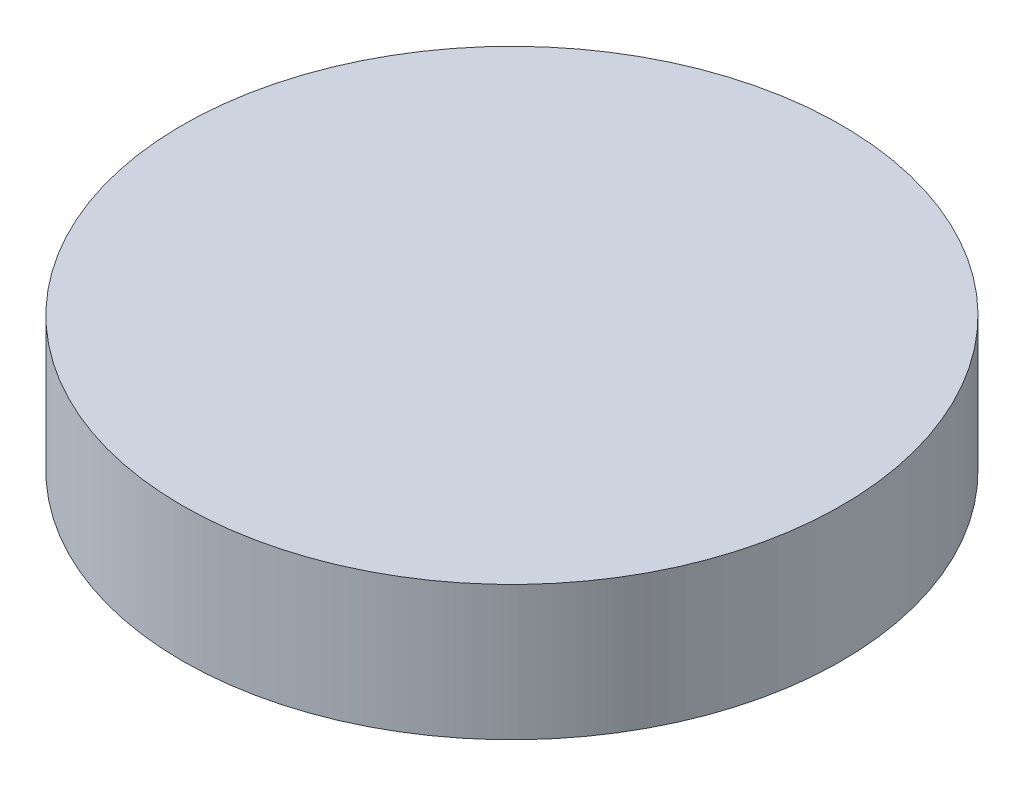
SolidWorks part; units mm, degrees
ref_plane "Front Plane" through (0, 0, 0) normal (0, 0, 1) x (1, 0, 0)
ref_plane "Top Plane" through (0, 0, 0) normal (0, 1, 0) x (1, 0, 0)
ref_plane "Right Plane" through (0, 0, 0) normal (1, 0, 0) x (0, 0, -1)
sketch "Sketch1" plane through (0, 0, 0) normal (0, 1, 0) x (1, 0, 0)
  circle A0 centre (0, 0) radius 12.25
  dimension "D1" = 24.5
extrude "Boss-Extrude1" add sketch "Sketch1" along normal blind 5
ref_plane "Plane1" through (0, 0, 12.25) normal (0, 0, 1) x (1, 0, 0)
ref_plane "Plane2" through (12.25, 0, 0) normal (1, 0, 0) x (0, 0, -1)
ref_plane "Plane3" through (-12.25, 0, 0) normal (-1, 0, 0) x (0, 0, 1)
ref_plane "Plane4" through (0, 0, -12.25) normal (0, 0, -1) x (-1, 0, 0)
